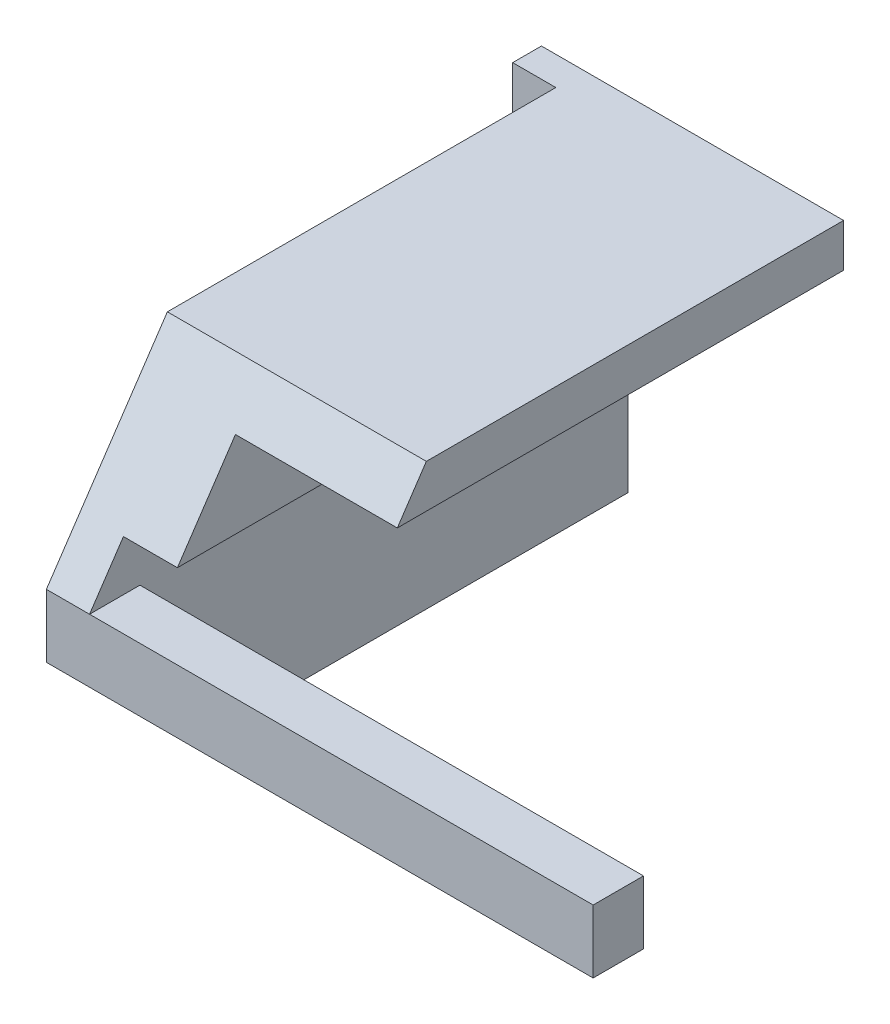
SolidWorks part; units mm, degrees
material "6061 合金"
ref_plane "前视基准面" through (0, 0, 0) normal (0, 0, 1) x (1, 0, 0)
ref_plane "上视基准面" through (0, 0, 0) normal (0, 1, 0) x (1, 0, 0)
ref_plane "右视基准面" through (0, 0, 0) normal (1, 0, 0) x (0, 0, -1)
sketch "草图1" plane through (0, 0, 0) normal (1, 0, 0) x (0, 0, -1)
  line L1 (-12.5, 12.5) -> (12.5, 12.5)
  line L2 (-12.5, 12.5) -> (-12.5, -12.5)
  line L3 (-12.5, -12.5) -> (12.5, -12.5)
  line L4 (12.5, 12.5) -> (12.5, -12.5)
  line L5 (-12.5, 12.5) -> (12.5, -12.5) construction
  line L6 (-12.5, -12.5) -> (12.5, 12.5) construction
  point P0 (0, 0)
  dimension "D1" = 25
  dimension "D2" = 25
sketch "草图2" plane through (0, 0, 0) normal (1, 0, 0) x (0, 0, -1)
  line L8 (14.5, 14.5) -> (-14.5, 14.5)
  line L9 (14.5, -14.5) -> (14.5, 14.5)
  line L10 (-14.5, -14.5) -> (14.5, -14.5)
  line L11 (-14.5, 14.5) -> (-14.5, -14.5)
  line L12 (14.5, 14.5) -> (-14.5, 14.5)
  line L13 (14.5, -14.5) -> (14.5, 14.5)
  line L14 (-14.5, -14.5) -> (14.5, -14.5)
  line L15 (-14.5, 14.5) -> (-14.5, -14.5)
  dimension "D1" = 2
extrude "凸台-拉伸1" add sketch "草图2" along normal blind 5 and the other way blind 3
sketch "草图3" plane through (-3, 0, 0) normal (-1, 0, 0) x (0, 0, 1)
  line L0 (12.5, 12.5) -> (12.5, -12.5) construction
  line L5 (12.5, -12.5) -> (-12.5, -12.5) construction
  line L6 (-12.5, 12.5) -> (-12.5, -12.5) construction
  line L7 (12.5, 12.5) -> (-12.5, 12.5) construction
  line L8 (12.5, 12.5) -> (12.5, -12.5)
  line L9 (12.5, -12.5) -> (-12.5, -12.5)
  line L10 (-12.5, 12.5) -> (-12.5, -12.5)
  line L11 (12.5, 12.5) -> (-12.5, 12.5)
extrude "切除-拉伸1" cut sketch "草图3" against normal blind 3
sketch "草图5" plane through (-3, 0, 0) normal (-1, 0, 0) x (0, 0, 1)
  circle A0 centre (-12.5, -12.5) radius 1
extrude "切除-拉伸3" cut sketch "草图5" against normal up to surface (3 mm away) up to face at (0, 0, 0)
sketch "草图6" plane through (-3, 0, 0) normal (-1, 0, 0) x (0, 0, 1)
  line L0 (12.5, 12.5) -> (12.5, -12.5) construction
  line L1 (12.5, 12.5) -> (-12.5, 12.5) construction
  line L2 (12.5, 12.5) -> (12.5, -12.5)
  line L3 (12.5, 12.5) -> (-12.5, 12.5)
  line L4 (14.5, 14.5) -> (14.5, -12.5)
  line L5 (14.5, 14.5) -> (-12.5, 14.5)
  line L6 (12.5, -12.5) -> (14.5, -12.5)
  line L7 (-14.5, 14.5) -> (-12.5, 14.5)
  line L8 (-14.5, 14.5) -> (-14.5, 12.5)
  line L9 (-14.5, 12.5) -> (-12.5, 12.5)
  dimension "D1" = 2
extrude "切除-拉伸4" cut sketch "草图6" against normal through all
hole_wizard "M4 螺纹孔1" positions "草图8" profile "草图9" tap size "M4" standard "GB"
sketch "草图8" plane through (0, 0, 0) normal (-1, 0, 0) x (0, 0, 1)
  point P0 (0, 0)
sketch "草图9" plane through (0, 0, 0) normal (0, 1, 0) x (0, 0, 1)
  line L0 (0, 0) -> (0, 11.0914)
  line L1 (0, 11.0914) -> (1.65, 10.1)
  line L2 (1.65, 10.1) -> (1.65, 0)
  line L5 (1.65, 0) -> (0, 0)
  line L10 (0, 11.0914) -> (-1.65, 10.1) construction
  line L11 (0, -6.35) -> (0, 107.95) construction
  dimension "螺纹孔钻头直径" = 3.3
  dimension "螺纹孔钻头深度" = 10.1
  dimension "导头角度" = 118
cosmetic thread "孔螺蚊线1" parameters "D1"=8, "D2"=4
sketch "草图4" plane through (0, -14.5, 0) normal (0, -1, 0) x (1, 0, 0)
  line L4 (-3, -14.5) -> (5, -14.5)
  line L5 (5, -14.5) -> (5, 14.5)
  line L6 (5, 14.5) -> (-3, 14.5)
  line L7 (-3, 14.5) -> (-3, -14.5)
  line L8 (-3, -14.5) -> (5, -14.5)
  line L9 (5, -14.5) -> (5, 14.5)
  line L10 (5, 14.5) -> (-3, 14.5)
  line L11 (-3, 14.5) -> (-3, -14.5)
  dimension "D1" = 0
extrude "凸台-拉伸2" add sketch "草图4" along normal blind 13.4052
sketch "草图7" plane through (5, 0, 0) normal (1, 0, 0) x (0, 0, -1)
  line L0 (-14.5, -12.5) -> (-14.5, -27.9052) construction
  line L1 (14.5, -27.9052) -> (-14.5, -27.9052)
  line L2 (14.5, -27.9052) -> (14.5, -22.9052)
  line L3 (14.5, -22.9052) -> (-14.5, -22.9052)
  line L4 (-14.5, -27.9052) -> (-14.5, -22.9052)
  dimension "D1" = 5
extrude "凸台-拉伸3" add sketch "草图7" along normal offset from surface (5 mm away) 10 up to face at (0, 0, 1.65)
sketch "草图10" plane through (-3, 0, 0) normal (-1, 0, 0) x (0, 0, 1)
  line L0 (-14.5, -27.9052) -> (-14.5, 12.5) construction
  line L1 (14.5, -27.9052) -> (-14.5, -27.9052)
  line L2 (14.5, -27.9052) -> (14.5, -14.5)
  line L3 (14.5, -14.5) -> (-14.5, -14.5)
  line L4 (-14.5, -27.9052) -> (-14.5, -14.5)
  line L5 (12.5, -12.5) -> (-12.5, -12.5) construction
  dimension "D1" = 2
extrude "切除-拉伸5" cut sketch "草图10" against normal through all
sketch "草图11" plane through (5, 0, 0) normal (1, 0, 0) x (0, 0, -1)
  line L6 (-14.5, -14.5) -> (14.5, -14.5)
  line L7 (14.5, -14.5) -> (14.5, 12.5)
  line L8 (14.5, 12.5) -> (-12.5, 12.5)
  line L9 (-12.5, 12.5) -> (-12.5, -12.5)
  line L10 (-12.5, -12.5) -> (-14.5, -12.5)
  line L11 (-14.5, -12.5) -> (-14.5, -14.5)
  line L12 (-14.5, -14.5) -> (14.5, -14.5)
  line L13 (14.5, -14.5) -> (14.5, 12.5)
  line L14 (14.5, 12.5) -> (-12.5, 12.5)
  line L15 (-12.5, 12.5) -> (-12.5, -12.5)
  line L16 (-12.5, -12.5) -> (-14.5, -12.5)
  line L17 (-14.5, -12.5) -> (-14.5, -14.5)
  dimension "D1" = 0
extrude "切除-拉伸6" [suppressed] cut sketch "草图11" against normal blind 2
sketch "草图12" plane through (5, 0, 0) normal (1, 0, 0) x (0, 0, -1)
  line L6 (-14.5, -14.5) -> (14.5, -14.5)
  line L7 (14.5, -14.5) -> (14.5, 12.5)
  line L8 (14.5, 12.5) -> (-12.5, 12.5)
  line L9 (-12.5, 12.5) -> (-12.5, -12.5)
  line L10 (-12.5, -12.5) -> (-14.5, -12.5)
  line L11 (-14.5, -12.5) -> (-14.5, -14.5)
  line L12 (-14.5, -14.5) -> (14.5, -14.5)
  line L13 (14.5, -14.5) -> (14.5, 12.5)
  line L14 (14.5, 12.5) -> (-12.5, 12.5)
  line L15 (-12.5, 12.5) -> (-12.5, -12.5)
  line L16 (-12.5, -12.5) -> (-14.5, -12.5)
  line L17 (-14.5, -12.5) -> (-14.5, -14.5)
  dimension "D1" = 0
extrude "凸台-拉伸4" add sketch "草图12" along normal blind 28
sketch "草图13" plane through (0, -14.5, 0) normal (0, -1, 0) x (1, 0, 0)
  line L0 (33, 14.5) -> (-3, 14.5) construction
  line L1 (33, -14.5) -> (10.5582, -14.5)
  line L2 (33, -14.5) -> (33, 14.5)
  line L3 (33, 14.5) -> (10.5582, 14.5)
  line L4 (10.5582, -14.5) -> (10.5582, 14.5)
extrude "切除-拉伸7" cut sketch "草图13" against normal blind 20.8948
sketch "草图14" plane through (33, 0, 0) normal (1, 0, 0) x (0, 0, -1)
  line L4 (-12.5, 12.5) -> (-12.5, 6.3948)
  line L5 (-12.5, 6.3948) -> (14.5, 6.3948)
  line L6 (14.5, 6.3948) -> (14.5, 12.5)
  line L7 (14.5, 12.5) -> (-12.5, 12.5)
  line L8 (-12.5, 12.5) -> (-12.5, 6.3948)
  line L9 (-12.5, 6.3948) -> (14.5, 6.3948)
  line L10 (14.5, 6.3948) -> (14.5, 12.5)
  line L11 (14.5, 12.5) -> (-12.5, 12.5)
  dimension "D1" = 0
extrude "切除-拉伸8" cut sketch "草图14" against normal blind 10
sketch "草图15" plane through (0, 0, 12.5) normal (0, 0, 1) x (1, 0, 0)
  line L0 (10.5582, -14.5) -> (-3, -14.5) construction
  line L6 (23, 6.3948) -> (23, 12.5)
  line L7 (23, 12.5) -> (0, 12.5)
  line L8 (0, 12.5) -> (0, -12.5)
  line L9 (0, -12.5) -> (10.5582, -12.5)
  line L10 (10.5582, -12.5) -> (10.5582, 6.3948)
  line L11 (10.5582, 6.3948) -> (23, 6.3948)
  line L12 (23, 6.3948) -> (23, 12.5)
  line L13 (23, 12.5) -> (0, 12.5)
  line L14 (0, 12.5) -> (0, -14.5)
  line L15 (0, -14.5) -> (23, -14.5)
  line L16 (23, -14.5) -> (23, 6.3948)
  dimension "D1" = 0
extrude "凸台-拉伸5" add sketch "草图15" along normal blind 10
sketch "草图16" plane through (0, 0, 12.5) normal (0, 0, -1) x (-1, 0, 0)
  line L4 (-10.5582, 6.3948) -> (-23, 6.3948)
  line L5 (-23, 6.3948) -> (-23, -14.5)
  line L6 (-23, -14.5) -> (-10.5582, -14.5)
  line L7 (-10.5582, -14.5) -> (-10.5582, 6.3948)
  line L8 (-10.5582, 6.3948) -> (-23, 6.3948)
  line L9 (-23, 6.3948) -> (-23, -14.5)
  line L10 (-23, -14.5) -> (-10.5582, -14.5)
  line L11 (-10.5582, -14.5) -> (-10.5582, 6.3948)
  dimension "D1" = 0
extrude "切除-拉伸9" cut sketch "草图16" against normal blind 5
sketch "草图17" plane through (23, 0, 0) normal (1, 0, 0) x (0, 0, -1)
  line L6 (-17.5, -14.5) -> (-17.5, 6.3948)
  line L7 (-17.5, 6.3948) -> (14.5, 6.3948)
  line L8 (14.5, 6.3948) -> (14.5, 12.5)
  line L9 (14.5, 12.5) -> (-22.5, 12.5)
  line L10 (-22.5, 12.5) -> (-22.5, -14.5)
  line L11 (-22.5, -14.5) -> (-17.5, -14.5)
  line L12 (-17.5, -14.5) -> (-17.5, 6.3948)
  line L13 (-17.5, 6.3948) -> (14.5, 6.3948)
  line L14 (14.5, 6.3948) -> (14.5, 12.5)
  line L15 (14.5, 12.5) -> (-22.5, 12.5)
  line L16 (-22.5, 12.5) -> (-22.5, -14.5)
  line L17 (-22.5, -14.5) -> (-17.5, -14.5)
  dimension "D1" = 0
extrude "切除-拉伸10" cut sketch "草图17" against normal blind 5
sketch "草图18" plane through (0, 0, 17.5) normal (0, 0, -1) x (-1, 0, 0)
  line L4 (-10.5582, 6.3948) -> (-18, 6.3948)
  line L5 (-18, 6.3948) -> (-18, -14.5)
  line L6 (-18, -14.5) -> (-10.5582, -14.5)
  line L7 (-10.5582, -14.5) -> (-10.5582, 6.3948)
  line L8 (-10.5582, 6.3948) -> (-18, 6.3948)
  line L9 (-18, 6.3948) -> (-18, -14.5)
  line L10 (-18, -14.5) -> (-10.5582, -14.5)
  line L11 (-10.5582, -14.5) -> (-10.5582, 6.3948)
  dimension "D1" = 0
extrude "切除-拉伸11" cut sketch "草图18" against normal blind 1.9069
sketch "草图19" plane through (0, -14.5, 0) normal (0, -1, 0) x (1, 0, 0)
  line L1 (0, 14.5) -> (18, 14.5)
  line L2 (0, 14.5) -> (0, 22.5)
  line L3 (0, 22.5) -> (18, 22.5)
  line L4 (18, 14.5) -> (18, 22.5)
extrude "切除-拉伸12" cut sketch "草图19" against normal blind 7
sketch "草图20" plane through (18, 0, 0) normal (1, 0, 0) x (0, 0, -1)
  line L0 (-22.5, 12.5) -> (-22.5, -7.5) construction
  line L1 (-19.4069, -7.5) -> (-22.5, -7.5)
  line L2 (-19.4069, -7.5) -> (-19.4069, 3.5)
  line L3 (-19.4069, 3.5) -> (-22.5, 3.5)
  line L4 (-22.5, -7.5) -> (-22.5, 3.5)
  dimension "D1" = 11
extrude "凸台-拉伸6" add sketch "草图20" along normal blind 20
sketch "草图21" plane through (18, 0, 0) normal (1, 0, 0) x (0, 0, -1)
  line L1 (-19.4069, 6.3948) -> (-22.5, 6.3948)
  line L2 (-19.4069, 6.3948) -> (-19.4069, 3.5)
  line L3 (-19.4069, 3.5) -> (-22.5, 3.5)
  line L4 (-22.5, 6.3948) -> (-22.5, 3.5)
extrude "切除-拉伸13" cut sketch "草图21" against normal up to surface (7.4418 mm away) up to face at (10.5582, -5.2017, 6.469)
sketch "草图22" plane through (10.5582, 0, 0) normal (1, 0, 0) x (0, 0, -1)
  line L1 (-14.5, -7.5) -> (14.5, -7.5)
  line L2 (-14.5, -7.5) -> (-14.5, -14.5)
  line L3 (-14.5, -14.5) -> (14.5, -14.5)
  line L4 (14.5, -7.5) -> (14.5, -14.5)
extrude "切除-拉伸14" cut sketch "草图22" against normal offset from surface (7.5582 mm away) 3 up to face at (0, -3.9582, 5.1847)
sketch "草图23" plane through (0, 0, 22.5) normal (0, 0, 1) x (1, 0, 0)
  line L8 (10.5582, 6.3948) -> (18, 6.3948)
  line L9 (18, 6.3948) -> (18, 12.5)
  line L10 (18, 12.5) -> (0, 12.5)
  line L11 (0, 12.5) -> (0, -7.5)
  line L12 (0, -7.5) -> (38, -7.5)
  line L13 (38, -7.5) -> (38, 3.5)
  line L14 (38, 3.5) -> (10.5582, 3.5)
  line L15 (10.5582, 3.5) -> (10.5582, 6.3948)
  line L16 (10.5582, 6.3948) -> (18, 6.3948)
  line L17 (18, 6.3948) -> (18, 12.5)
  line L18 (18, 12.5) -> (0, 12.5)
  line L19 (0, 12.5) -> (0, -7.5)
  line L20 (0, -7.5) -> (38, -7.5)
  line L21 (38, -7.5) -> (38, 3.5)
  line L22 (38, 3.5) -> (10.5582, 3.5)
  line L23 (10.5582, 3.5) -> (10.5582, 6.3948)
  dimension "D1" = 0
extrude "凸台-拉伸7" add sketch "草图23" along normal blind 3
sketch "草图24" plane through (0, -7.5, 0) normal (0, -1, 0) x (1, 0, 0)
  line L0 (0, 25.5) -> (38, 25.5) construction
  line L1 (0, 14.5) -> (3, 14.5)
  line L2 (0, 14.5) -> (0, 25.5)
  line L3 (0, 25.5) -> (3, 25.5)
  line L4 (3, 14.5) -> (3, 25.5)
  line L5 (3, 14.5) -> (3, -14.5) construction
extrude "切除-拉伸15" cut sketch "草图24" against normal through all
fillet "圆角2" [suppressed] radius 5
sketch "草图25" plane through (10.5582, 0, 0) normal (1, 0, 0) x (0, 0, -1)
  line L6 (-19.4069, -7.5) -> (14.5, -7.5)
  line L7 (14.5, -7.5) -> (14.5, 6.3948)
  line L8 (14.5, 6.3948) -> (-25.5, 6.3948)
  line L9 (-25.5, 6.3948) -> (-25.5, 3.5)
  line L10 (-25.5, 3.5) -> (-19.4069, 3.5)
  line L11 (-19.4069, 3.5) -> (-19.4069, -7.5)
  line L12 (-19.4069, -7.5) -> (14.5, -7.5)
  line L13 (14.5, -7.5) -> (14.5, 6.3948)
  line L14 (14.5, 6.3948) -> (-25.5, 6.3948)
  line L15 (-25.5, 6.3948) -> (-25.5, 3.5)
  line L16 (-25.5, 3.5) -> (-19.4069, 3.5)
  line L17 (-19.4069, 3.5) -> (-19.4069, -7.5)
  dimension "D1" = 0
extrude "切除-拉伸16" cut sketch "草图25" against normal blind 3.8082
sketch "草图26" plane through (0, 0, 25.5) normal (0, 0, 1) x (1, 0, 0)
  line L0 (18, 12.5) -> (3, 12.5) construction
  line L1 (6.75, 6.3948) -> (18, 6.3948)
  line L2 (6.75, 6.3948) -> (6.75, 12.5)
  line L3 (6.75, 12.5) -> (18, 12.5)
  line L4 (18, 6.3948) -> (18, 12.5)
extrude "切除-拉伸17" cut sketch "草图26" against normal up to surface (6.0931 mm away)
sketch "草图27" plane through (6.75, 0, 0) normal (1, 0, 0) x (0, 0, -1)
  line L1 (-19.4069, 6.3948) -> (-25.5, 6.3948)
  line L2 (-19.4069, 6.3948) -> (-19.4069, 12.5)
  line L3 (-19.4069, 12.5) -> (-25.5, 12.5)
  line L4 (-25.5, 6.3948) -> (-25.5, 12.5)
extrude "切除-拉伸18" cut sketch "草图27" against normal through all
sketch "草图28" plane through (0, 12.5, 0) normal (0, 1, 0) x (1, 0, 0)
  line L7 (3, -14.5) -> (3, -19.4069)
  line L8 (3, -19.4069) -> (18, -19.4069)
  line L9 (18, -19.4069) -> (18, 14.5)
  line L10 (18, 14.5) -> (-3, 14.5)
  line L11 (-3, 14.5) -> (-3, 12.5)
  line L12 (-3, 12.5) -> (0, 12.5)
  line L13 (0, 12.5) -> (0, -14.5)
  line L14 (3, -14.5) -> (3, -19.4069)
  line L15 (3, -19.4069) -> (18, -19.4069)
  line L16 (18, -19.4069) -> (18, 14.5)
  line L17 (18, 14.5) -> (-3, 14.5)
  line L18 (-3, 14.5) -> (-3, 12.5)
  line L19 (-3, 12.5) -> (0, 12.5)
  line L20 (0, 12.5) -> (0, -14.5)
  line L22 (0, -14.5) -> (3, -14.5)
  line L23 (0, -14.5) -> (3, -14.5)
  dimension "D1" = 0
extrude "切除-拉伸19" cut sketch "草图28" against normal offset from surface (3.1052 mm away) 3
sketch "草图29" plane through (0, 0, 25.5) normal (0, 0, 1) x (1, 0, 0)
  line L6 (6.75, 3.5) -> (6.75, 6.3948)
  line L7 (6.75, 6.3948) -> (3, 6.3948)
  line L8 (3, 6.3948) -> (3, -7.5)
  line L9 (3, -7.5) -> (38, -7.5)
  line L10 (38, -7.5) -> (38, 3.5)
  line L11 (38, 3.5) -> (6.75, 3.5)
  line L12 (6.75, 3.5) -> (6.75, 6.3948)
  line L13 (6.75, 6.3948) -> (3, 6.3948)
  line L14 (3, 6.3948) -> (3, -7.5)
  line L15 (3, -7.5) -> (38, -7.5)
  line L16 (38, -7.5) -> (38, 3.5)
  line L17 (38, 3.5) -> (6.75, 3.5)
  dimension "D1" = 0
sketch "草图30" plane through (0, -7.5, 0) normal (0, -1, 0) x (1, 0, 0)
  line L1 (3, 18.221) -> (6.75, 18.221)
  line L2 (3, 18.221) -> (3, -14.5)
  line L3 (3, -14.5) -> (6.75, -14.5)
  line L4 (6.75, 18.221) -> (6.75, -14.5)
  point P4 (0, 0)
extrude "切除-拉伸20" cut sketch "草图30" against normal offset from surface (7.8948 mm away) 6 up to face at (12.375, 6.3948, 2.4534)
sketch "草图31" plane through (0, 0, 19.4069) normal (0, 0, 1) x (1, 0, 0)
  line L5 (18, 6.3948) -> (18, 9.3948)
  line L6 (18, 9.3948) -> (3, 9.3948)
  line L7 (3, 9.3948) -> (3, 6.3948)
  line L8 (3, 6.3948) -> (6.75, 6.3948)
  line L9 (6.75, 6.3948) -> (18, 6.3948)
  line L10 (18, 6.3948) -> (18, 9.3948)
  line L11 (18, 9.3948) -> (3, 9.3948)
  line L12 (3, 9.3948) -> (3, 6.3948)
  line L13 (3, 6.3948) -> (6.75, 6.3948)
  line L14 (6.75, 6.3948) -> (18, 6.3948)
  dimension "D1" = 0
extrude "切除-拉伸21" cut sketch "草图31" against normal up to surface (4.9069 mm away) up to face at (0.4286, -4.9737, 14.5)
sketch "草图32" plane through (0, 3.5, 0) normal (0, 1, 0) x (1, 0, 0)
  line L4 (38, -19.4069) -> (6.75, -19.4069)
  line L5 (6.75, -19.4069) -> (6.75, -25.5)
  line L6 (6.75, -25.5) -> (38, -25.5)
  line L7 (38, -25.5) -> (38, -19.4069)
  line L8 (38, -19.4069) -> (6.75, -19.4069)
  line L9 (6.75, -19.4069) -> (6.75, -25.5)
  line L10 (6.75, -25.5) -> (38, -25.5)
  line L11 (38, -25.5) -> (38, -19.4069)
  dimension "D1" = 0
extrude "切除-拉伸22" cut sketch "草图32" against normal blind 3.5
sketch "草图33" plane through (3, 0, 0) normal (-1, 0, 0) x (0, 0, 1)
  line L1 (25.5, -7.5) -> (14.5, -7.5)
  line L2 (25.5, -7.5) -> (25.5, 6.3948)
  line L3 (25.5, 6.3948) -> (14.5, 6.3948)
  line L4 (14.5, -7.5) -> (14.5, 6.3948)
extrude "凸台-拉伸8" add sketch "草图33" along normal up to surface (3 mm away) up to face at (0, -3.7835, -1.7414)
sketch "草图34" plane through (0, 0, 0) normal (1, 0, 0) x (0, 0, -1)
  line L0 (-25.5, 6.3948) -> (-25.5, -7.5) construction
  line L1 (-14.5, 6.3948) -> (-25.5, 6.3948)
  line L2 (-14.5, 6.3948) -> (-14.5, 0)
  line L3 (-14.5, 0) -> (-25.5, 0)
  line L4 (-25.5, 6.3948) -> (-25.5, 0)
  line L5 (22, 0) -> (-22, 0) construction
extrude "切除-拉伸25" cut sketch "草图34" along normal through all
sketch "草图35" plane through (0, 0, 0) normal (0, 1, 0) x (1, 0, 0)
  line L8 (38, -25.5) -> (38, -19.4069)
  line L9 (38, -19.4069) -> (6.75, -19.4069)
  line L10 (6.75, -19.4069) -> (6.75, -18.221)
  line L11 (6.75, -18.221) -> (3, -18.221)
  line L12 (3, -18.221) -> (3, -14.5)
  line L13 (3, -14.5) -> (0, -14.5)
  line L14 (0, -14.5) -> (0, -25.5)
  line L15 (0, -25.5) -> (38, -25.5)
  line L16 (38, -25.5) -> (38, -19.4069)
  line L17 (38, -19.4069) -> (6.75, -19.4069)
  line L18 (6.75, -19.4069) -> (6.75, -18.221)
  line L19 (6.75, -18.221) -> (3, -18.221)
  line L20 (3, -18.221) -> (3, -14.5)
  line L21 (3, -14.5) -> (0, -14.5)
  line L22 (0, -14.5) -> (0, -25.5)
  line L23 (0, -25.5) -> (38, -25.5)
  dimension "D1" = 0
extrude "凸台-拉伸9" add sketch "草图35" along normal up to surface (0.3948 mm away) up to face at (4.4375, 0.3948, 0)
sketch "草图36" plane through (0, 0, 25.5) normal (0, 0, 1) x (1, 0, 0)
  line L4 (38, -7.5) -> (38, 0.3948)
  line L5 (38, 0.3948) -> (0, 0.3948)
  line L6 (0, 0.3948) -> (0, -7.5)
  line L7 (0, -7.5) -> (38, -7.5)
  line L8 (38, -7.5) -> (38, 0.3948)
  line L9 (38, 0.3948) -> (0, 0.3948)
  line L10 (0, 0.3948) -> (0, -7.5)
  line L11 (0, -7.5) -> (38, -7.5)
  dimension "D1" = 0
extrude "切除-拉伸26" cut sketch "草图36" against normal offset from surface (2.5931 mm away) 3.5
sketch "草图37" plane through (0, 0.3948, 0) normal (0, 1, 0) x (1, 0, 0)
  line L0 (0, -14.5) -> (0, -22.9069) construction
  line L1 (0, -22.9069) -> (38, -22.9069) construction
  line L2 (38, -22.9069) -> (38, -19.4069) construction
  line L3 (38, -19.4069) -> (6.75, -19.4069) construction
  line L4 (6.75, -19.4069) -> (6.75, -18.221) construction
  line L5 (6.75, -18.221) -> (3, -18.221) construction
  line L6 (3, -18.221) -> (3, -14.5) construction
  line L7 (3, -14.5) -> (0, -14.5) construction
  line L8 (38, -19.4069) -> (38, -22.9069) construction
  line L9 (38, -22.9069) -> (0, -22.9069) construction
  line L10 (0, -22.9069) -> (0, -14.5) construction
  line L11 (0, -14.5) -> (3, -14.5) construction
  line L12 (3, -14.5) -> (3, -18.221) construction
  line L13 (3, -18.221) -> (6.75, -18.221) construction
  line L14 (6.75, -18.221) -> (6.75, -19.4069) construction
  line L15 (6.75, -19.4069) -> (38, -19.4069) construction
  line L16 (0, -14.5) -> (0, -22.9069)
  line L17 (0, -22.9069) -> (38, -22.9069)
  line L18 (38, -22.9069) -> (38, -19.4069)
  line L19 (38, -19.4069) -> (6.75, -19.4069)
  line L20 (6.75, -19.4069) -> (6.75, -18.221)
  line L21 (6.75, -18.221) -> (3, -18.221)
  line L22 (3, -18.221) -> (3, -14.5)
  line L23 (3, -14.5) -> (0, -14.5)
  line L24 (38, -19.4069) -> (38, -22.9069)
  line L25 (38, -22.9069) -> (0, -22.9069)
  line L26 (0, -22.9069) -> (0, -14.5)
  line L27 (0, -14.5) -> (3, -14.5)
  line L28 (3, -14.5) -> (3, -18.221)
  line L29 (3, -18.221) -> (6.75, -18.221)
  line L30 (6.75, -18.221) -> (6.75, -19.4069)
  line L31 (6.75, -19.4069) -> (38, -19.4069)
  line M1 (0, -14.5) -> (0, -22.9069)
  line M2 (0, -22.9069) -> (38, -22.9069)
  line M3 (38, -22.9069) -> (38, -19.4069)
  line M4 (38, -19.4069) -> (6.75, -19.4069)
  line M5 (6.75, -19.4069) -> (6.75, -18.221)
  line M6 (6.75, -18.221) -> (3, -18.221)
  line M7 (3, -18.221) -> (3, -14.5)
  line M8 (3, -14.5) -> (0, -14.5)
extrude "切除-拉伸27" cut sketch "草图37" against normal blind 3.5 contours M8 M1 M2 M3 M4 M5 M6 M7
sketch "草图38" plane through (6.75, 0, 0) normal (1, 0, 0) x (0, 0, -1)
  line L4 (-18.221, -7.5) -> (-18.221, -3.1052)
  line L5 (-18.221, -3.1052) -> (-19.4069, -3.1052)
  line L6 (-19.4069, -3.1052) -> (-19.4069, -7.5)
  line L7 (-19.4069, -7.5) -> (-18.221, -7.5)
  line L8 (-18.221, -7.5) -> (-18.221, -3.1052)
  line L9 (-18.221, -3.1052) -> (-19.4069, -3.1052)
  line L10 (-19.4069, -3.1052) -> (-19.4069, -7.5)
  line L11 (-19.4069, -7.5) -> (-18.221, -7.5)
  dimension "D1" = 0
extrude "切除-拉伸28" cut sketch "草图38" against normal up to surface (3.75 mm away) up to face at (3, -5.0676, 6.5442)
sketch "草图39" plane through (3, 0, 0) normal (1, 0, 0) x (0, 0, -1)
  line L0 (-14.5, 9.3948) -> (-14.5, -14.5)
  line L3 (-22.9069, -3.1052) -> (-22.9069, -7.5)
  line L5 (-22.9069, -3.1052) -> (-22.9069, -7.5) construction
  line L6 (-14.5, 9.3948) -> (-22.9069, -3.1052)
  line L7 (-22.9069, -7.5) -> (-14.5, -14.5)
extrude "凸台-拉伸11" add sketch "草图39" against normal up to surface (3 mm away) up to face at (0, -4.4587, 7.3452)
sketch "草图40" plane through (0, 0, 14.5) normal (0, 0, 1) x (1, 0, 0)
  line L6 (3, 9.3948) -> (3, 0.3948)
  line L7 (3, 0.3948) -> (6.75, 0.3948)
  line L8 (6.75, 0.3948) -> (6.75, 6.3948)
  line L9 (6.75, 6.3948) -> (18, 6.3948)
  line L10 (18, 6.3948) -> (18, 9.3948)
  line L11 (18, 9.3948) -> (3, 9.3948)
  line L12 (3, 9.3948) -> (3, 0.3948)
  line L13 (3, 0.3948) -> (6.75, 0.3948)
  line L14 (6.75, 0.3948) -> (6.75, 6.3948)
  line L15 (6.75, 6.3948) -> (18, 6.3948)
  line L16 (18, 6.3948) -> (18, 9.3948)
  line L17 (18, 9.3948) -> (3, 9.3948)
  dimension "D1" = 0
extrude "凸台-拉伸12" add sketch "草图40" along normal up to surface (2.0176 mm away)
